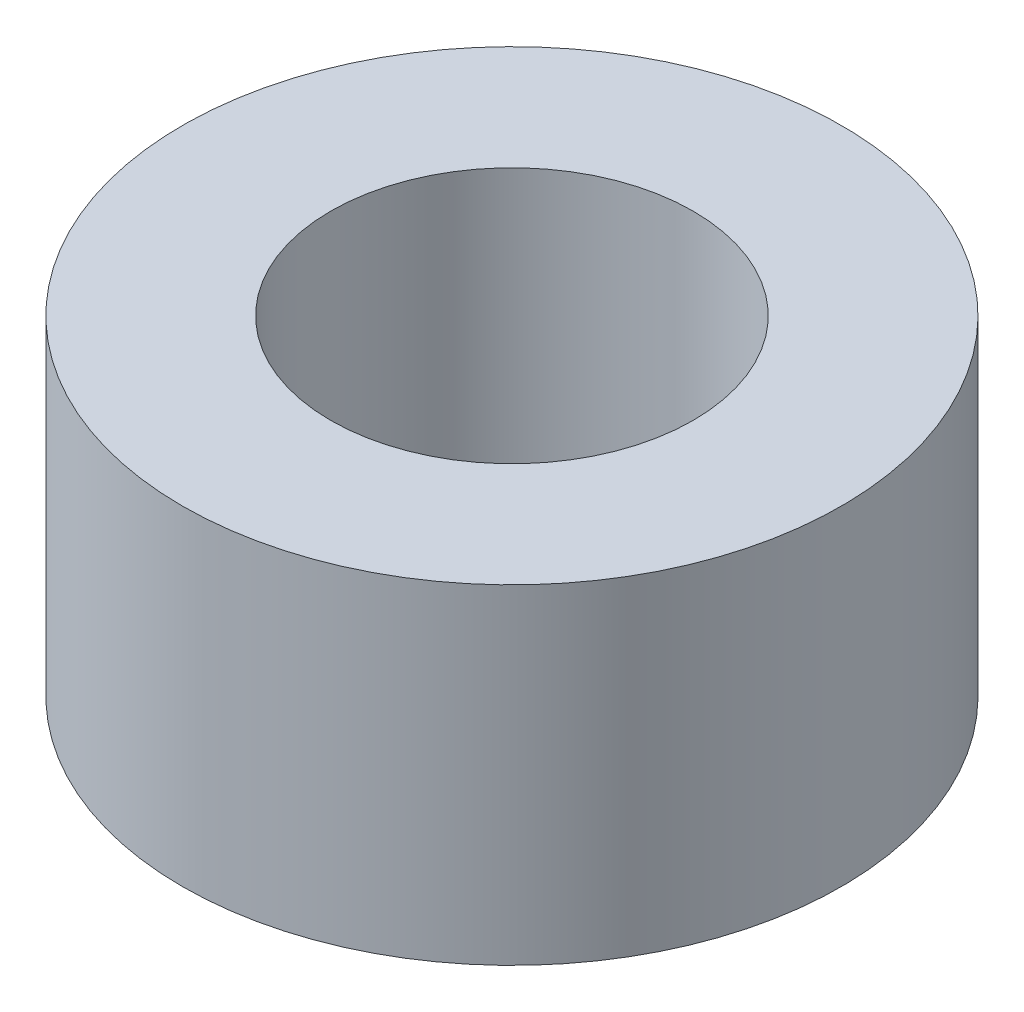
SolidWorks part; units mm, degrees
ref_plane "前视基准面" through (0, 0, 0) normal (0, 0, 1) x (1, 0, 0)
ref_plane "上视基准面" through (0, 0, 0) normal (0, 1, 0) x (1, 0, 0)
ref_plane "右视基准面" through (0, 0, 0) normal (1, 0, 0) x (0, 0, -1)
sketch "草图1" plane through (0, 0, 0) normal (0, 1, 0) x (1, 0, 0)
  circle A0 centre (0, 0) radius 1.65
  circle A1 centre (0, 0) radius 3
  dimension "D1" = 6
  dimension "D2" = 3.3
extrude "凸台-拉伸1" add sketch "草图1" along normal blind 3
